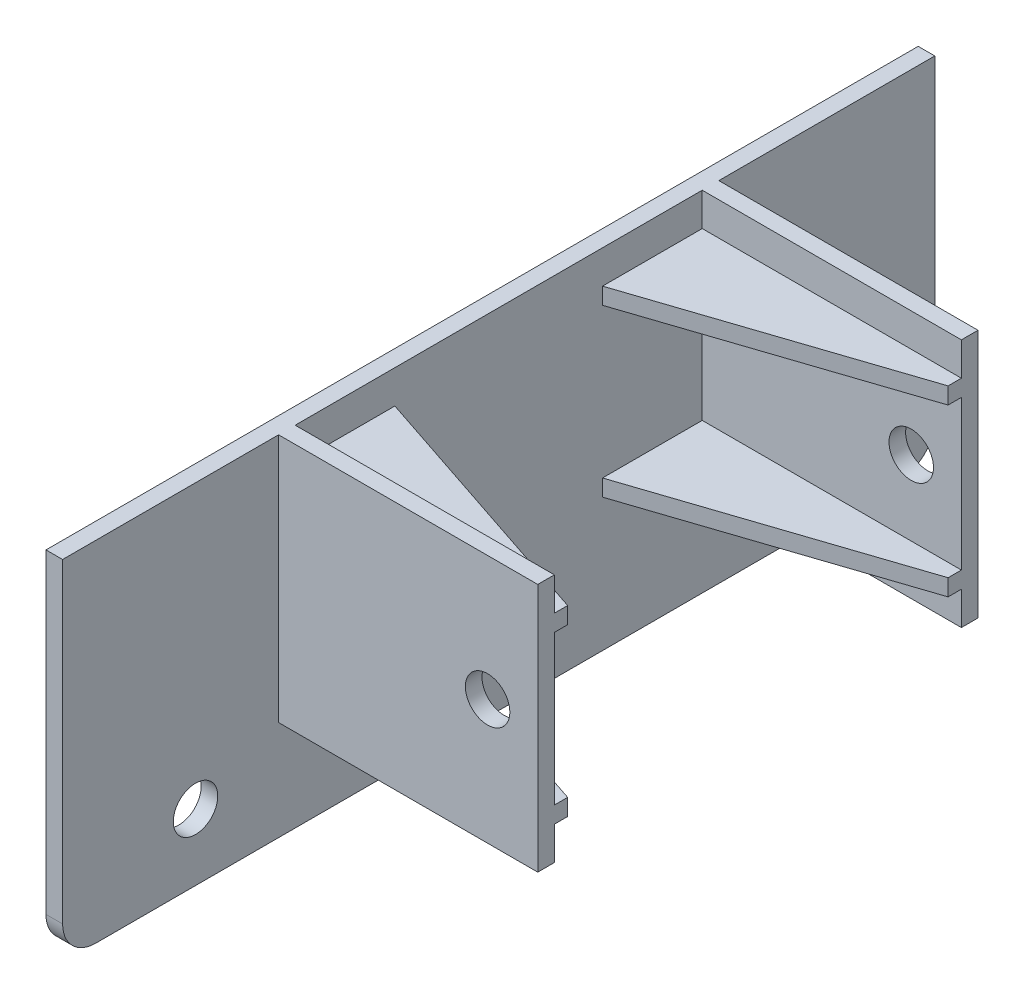
SolidWorks part; units mm, degrees
ref_plane "Front Plane" through (0, 0, 0) normal (0, 0, 1) x (1, 0, 0)
ref_plane "Top Plane" through (0, 0, 0) normal (0, 1, 0) x (1, 0, 0)
ref_plane "Right Plane" through (0, 0, 0) normal (1, 0, 0) x (0, 0, -1)
sketch "Sketch2" plane through (0, 0, 0) normal (0, 0, 1) x (1, 0, 0)
  line L1 (0, 0) -> (-1.27, 0)
  line L2 (0, 0) -> (0, 25.4)
  line L4 (-1.27, 0) -> (-1.27, 26.67)
  line L5 (-1.27, 26.67) -> (25.4, 26.67)
  line L7 (0, 25.4) -> (25.4, 25.4)
  line L8 (25.4, 26.67) -> (25.4, 25.4)
  dimension "D1" = 1.27
  dimension "D2" = 25.4
  dimension "D3" = 1.27
  dimension "D4" = 25.4
extrude "Boss-Extrude1" add sketch "Sketch2" along normal blind 66.675 contours L2 L7 L8 L5 L4 L1
sketch "Sketch3" plane through (-1.27, 0, 0) normal (-1, 0, 0) x (0, 0, 1)
  line L0 (33.3375, 0) -> (33.3375, 31.5293) construction
  line L1 (66.675, 0) -> (0, 0) construction
  circle A0 centre (10.16, 5.08) radius 1.7
  circle A1 centre (56.515, 5.08) radius 1.7
  dimension "D3" = 3.4
  dimension "D1" = 10.16
  dimension "D2" = 5.08
extrude "Cut-Extrude1" cut sketch "Sketch3" against normal through all
sketch "Sketch6" plane through (0, 26.67, 0) normal (0, 1, 0) x (1, 0, 0)
  line L0 (-1.27, -33.3375) -> (29.2999, -33.3375) construction
  line L1 (-1.27, -66.675) -> (-1.27, 0) construction
  circle A0 centre (20.32, -10.16) radius 1.7
  circle A1 centre (20.32, -56.515) radius 1.7
  dimension "D1" = 5.08
  dimension "D3" = 3.4
  dimension "D2" = 10.16
extrude "Cut-Extrude2" cut sketch "Sketch6" against normal through all
fillet "Fillet1" radius 2.54 4 edges at (25.4, 26.035, 0) (-0.635, 0, 0) (-0.635, 0, 66.675) (25.4, 26.035, 66.675)
sketch "Sketch8" plane through (0, 25.4, 0) normal (0, -1, 0) x (1, 0, 0)
  line L0 (25.4, 64.135) -> (25.4, 2.54) construction
  line L1 (22.86, 50.165) -> (0, 50.165)
  line L2 (22.86, 50.165) -> (22.86, 48.895)
  line L3 (22.86, 48.895) -> (0, 48.895)
  line L4 (0, 50.165) -> (0, 48.895)
  line L5 (0, 66.675) -> (0, 0) construction
  line L6 (25.4, 33.3375) -> (-1.27, 33.3375) construction
  line L7 (-1.27, 64.135) -> (-1.27, 2.54) construction
  line L8 (22.86, 17.78) -> (0, 17.78)
  line L9 (0, 16.51) -> (0, 17.78)
  line L10 (22.86, 16.51) -> (0, 16.51)
  line L11 (22.86, 16.51) -> (22.86, 17.78)
  circle A0 centre (20.32, 56.515) radius 1.7 construction
  dimension "D1" = 1.27
  dimension "D2" = 6.35
  dimension "D3" = 22.86
extrude "Boss-Extrude2" add sketch "Sketch8" along normal blind 17.78
sketch "Sketch12" plane through (0, 25.4, 0) normal (0, -1, 0) x (1, 0, 0)
  line L0 (0, 50.165) -> (22.86, 50.165)
  line L1 (22.86, 50.165) -> (22.86, 48.895)
  line L2 (22.86, 48.895) -> (0, 48.895)
  line L3 (0, 48.895) -> (0, 17.78)
  line L4 (0, 17.78) -> (22.86, 17.78)
  line L5 (22.86, 17.78) -> (22.86, 16.51)
  line L6 (22.86, 16.51) -> (0, 16.51)
  line L7 (0, 16.51) -> (0, 0)
  line L8 (0, 0) -> (31.8758, 0)
  line L9 (31.8758, 0) -> (31.8758, 66.675)
  line L10 (31.8758, 66.675) -> (0, 66.675)
  line L11 (0, 66.675) -> (0, 50.165)
extrude "Cut-Extrude5" cut sketch "Sketch12" against normal blind 17.78
sketch "Sketch13" plane through (0, 0, 0) normal (1, 0, 0) x (0, 0, -1)
  line L0 (-48.895, 7.62) -> (-48.895, 26.67) construction
  line L1 (-48.895, 10.16) -> (-41.275, 10.16)
  line L2 (-48.895, 10.16) -> (-48.895, 11.43)
  line L3 (-48.895, 11.43) -> (-41.275, 11.43)
  line L4 (-41.275, 10.16) -> (-41.275, 11.43)
  line L5 (-33.3375, 26.67) -> (-33.3375, -8.4227) construction
  line L6 (-17.78, 26.67) -> (-48.895, 26.67) construction
  line L7 (-17.78, 11.43) -> (-25.4, 11.43)
  line L8 (-25.4, 10.16) -> (-25.4, 11.43)
  line L9 (-17.78, 10.16) -> (-25.4, 10.16)
  line L10 (-17.78, 10.16) -> (-17.78, 11.43)
  line L11 (-48.895, 17.145) -> (6.8544, 17.145) construction
  line L12 (-17.78, 24.13) -> (-17.78, 22.86)
  line L13 (-17.78, 24.13) -> (-25.4, 24.13)
  line L14 (-25.4, 24.13) -> (-25.4, 22.86)
  line L15 (-17.78, 22.86) -> (-25.4, 22.86)
  line L16 (-48.895, 22.86) -> (-41.275, 22.86)
  line L17 (-41.275, 24.13) -> (-41.275, 22.86)
  line L18 (-48.895, 24.13) -> (-41.275, 24.13)
  line L19 (-48.895, 24.13) -> (-48.895, 22.86)
  dimension "D1" = 1.27
  dimension "D2" = 2.54
  dimension "D3" = 7.62
extrude "Boss-Extrude3" add sketch "Sketch13" along normal blind 22.86
sketch "Sketch14" plane through (0, 10.16, 0) normal (0, -1, 0) x (1, 0, 0)
  line L0 (0, 41.275) -> (22.86, 41.275)
  line L1 (22.86, 41.275) -> (22.86, 48.895)
  line L2 (22.86, 48.895) -> (0, 41.275)
  line L3 (0, 33.3375) -> (21.8623, 33.3375) construction
  line L4 (0, 64.135) -> (0, 2.54) construction
  line L5 (22.86, 25.4) -> (22.86, 17.78)
  line L6 (0, 25.4) -> (22.86, 25.4)
  line L7 (22.86, 17.78) -> (0, 25.4)
extrude "Cut-Extrude6" cut sketch "Sketch14" against normal blind 22.86
sketch "Sketch15" plane through (0, 0, 50.165) normal (0, 0, 1) x (1, 0, 0)
  circle A0 centre (15.9784, 17.145) radius 1.7
  dimension "D1" = 3.4
extrude "Cut-Extrude7" cut sketch "Sketch15" against normal blind 43.18
sketch "Sketch16" plane through (0, 26.67, 0) normal (0, 1, 0) x (1, 0, 0)
  line L0 (22.86, -50.165) -> (0, -50.165) construction
  line L1 (22.86, -16.51) -> (19.812, -16.51)
  line L2 (22.86, -16.51) -> (22.86, -50.165)
  line L3 (22.86, -50.165) -> (19.812, -50.165)
  line L4 (19.812, -16.51) -> (19.812, -50.165)
  dimension "D1" = 3.048
extrude "Cut-Extrude8" cut sketch "Sketch16" against normal blind 43.18
